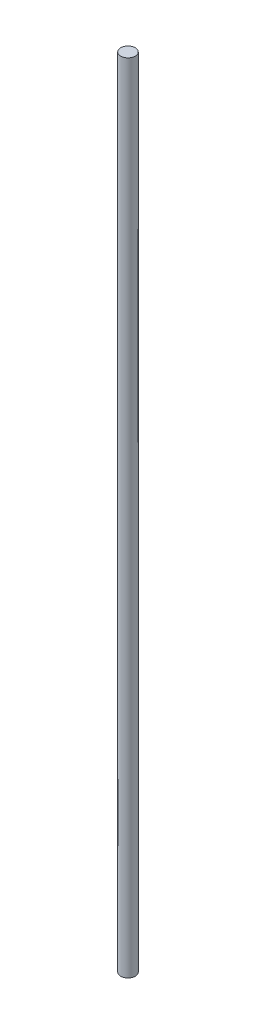
SolidWorks part; units mm, degrees
ref_plane "Front Plane" through (0, 0, 0) normal (0, 0, 1) x (1, 0, 0)
ref_plane "Top Plane" through (0, 0, 0) normal (0, 1, 0) x (1, 0, 0)
ref_plane "Right Plane" through (0, 0, 0) normal (1, 0, 0) x (0, 0, -1)
sketch "Sketch1" plane through (0, 0, 0) normal (0, 1, 0) x (1, 0, 0)
  circle A0 centre (0, 0) radius 2.5
  dimension "D1" = 5
extrude "Boss-Extrude1" add sketch "Sketch1" along normal blind 274.2
